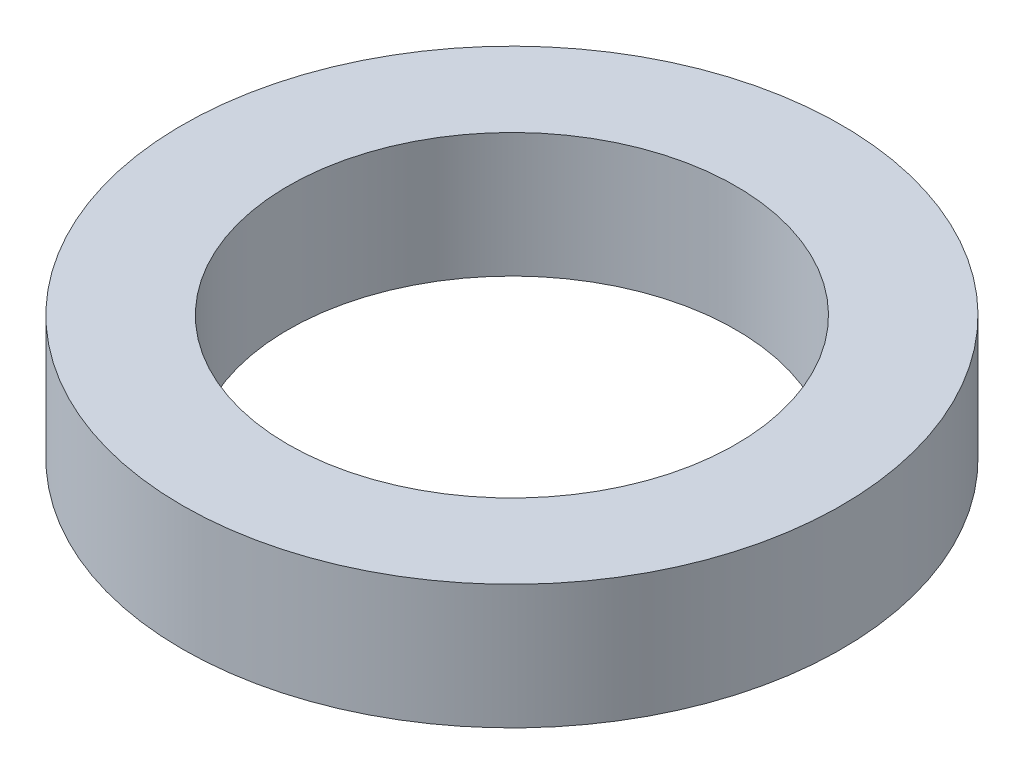
SolidWorks part; units mm, degrees
ref_plane "Front Plane" through (0, 0, 0) normal (0, 0, 1) x (1, 0, 0)
ref_plane "Top Plane" through (0, 0, 0) normal (0, 1, 0) x (1, 0, 0)
ref_plane "Right Plane" through (0, 0, 0) normal (1, 0, 0) x (0, 0, -1)
sketch "Sketch1" plane through (0, 0, 0) normal (0, 1, 0) x (1, 0, 0)
  circle A0 centre (0, 0) radius 6.731
  circle A1 centre (0, 0) radius 4.572
  dimension "D1" = 13.462
  dimension "D2" = 9.144
extrude "Boss-Extrude1" add sketch "Sketch1" along normal blind 2.54
